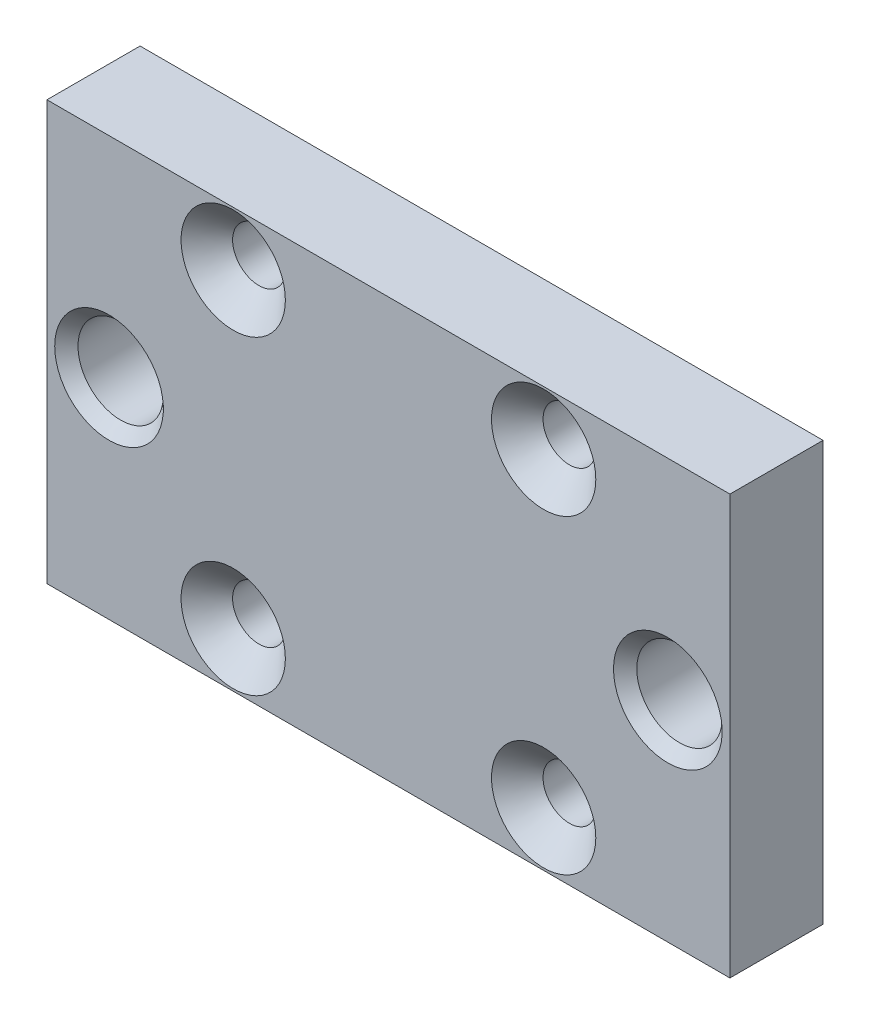
SolidWorks part; units mm, degrees
material "PET"
ref_plane "Front Plane" through (0, 0, 0) normal (0, 0, 1) x (1, 0, 0)
ref_plane "Top Plane" through (0, 0, 0) normal (0, 1, 0) x (1, 0, 0)
ref_plane "Right Plane" through (0, 0, 0) normal (1, 0, 0) x (0, 0, -1)
sketch "Sketch1" plane through (0, 0, 0) normal (0, 0, 1) x (1, 0, 0)
  line L0 (-22, 0) -> (22, 0) construction
  line L1 (22, 13.5) -> (-22, 13.5)
  line L2 (22, 13.5) -> (22, -13.5)
  line L3 (22, -13.5) -> (-22, -13.5)
  line L4 (-22, 13.5) -> (-22, -13.5)
  line L5 (22, 13.5) -> (-22, -13.5) construction
  line L6 (22, -13.5) -> (-22, 13.5) construction
  line L7 (10, 10) -> (-10, 10) construction
  line L8 (10, 10) -> (10, -10) construction
  line L9 (10, -10) -> (-10, -10) construction
  line L10 (-10, 10) -> (-10, -10) construction
  line L11 (10, 10) -> (-10, -10) construction
  line L12 (10, -10) -> (-10, 10) construction
  circle A0 centre (-18, 0) radius 2.75
  circle A1 centre (18, 0) radius 2.75
  point P1 (0, 0)
  point P6 (0, 0)
  dimension "D5" = 5.5
  dimension "D6" = 5.5
  dimension "D7" = 36
  dimension "D8" = 4
  dimension "D1" = 27
  dimension "D2" = 44
  dimension "D3" = 20
  dimension "D4" = 20
extrude "Boss-Extrude1" add sketch "Sketch1" along normal blind 6
hole_wizard "CSK for M3 SFHCS1" positions "Sketch2" profile "Sketch3" countersink size "M3" standard "ANSI Metric" end condition through all
sketch "Sketch2" plane through (0, 0, 6) normal (0, 0, 1) x (1, 0, 0)
  point P0 (-10, 10)
  point P3 (10, 10)
  point P6 (10, -10)
  point P9 (-10, -10)
sketch "Sketch3" plane through (-10, 10, 6) normal (1, 0, 0) x (0, -1, 0)
  line L0 (0, 0) -> (0, 6)
  line L1 (0, 6) -> (1.7, 6)
  line L2 (1.7, 6) -> (1.7, 1.66)
  line L3 (1.7, 1.66) -> (3.36, 0)
  line L5 (3.36, 0) -> (0, 0)
  line L6 (-1.7, 1.66) -> (-3.36, 0) construction
  line L11 (0, -6.35) -> (0, 107.95) construction
  dimension "Thru Hole Dia." = 3.4
  dimension "Thru Hole Depth" = 6
  dimension "Near C'Sink Dia." = 6.72
  dimension "Near C'Sink Angle" = 90
chamfer "Chamfer1" distance 0.75 angle 45 2 edges at (20.75, 0, 6) (-15.25, 0, 6)
